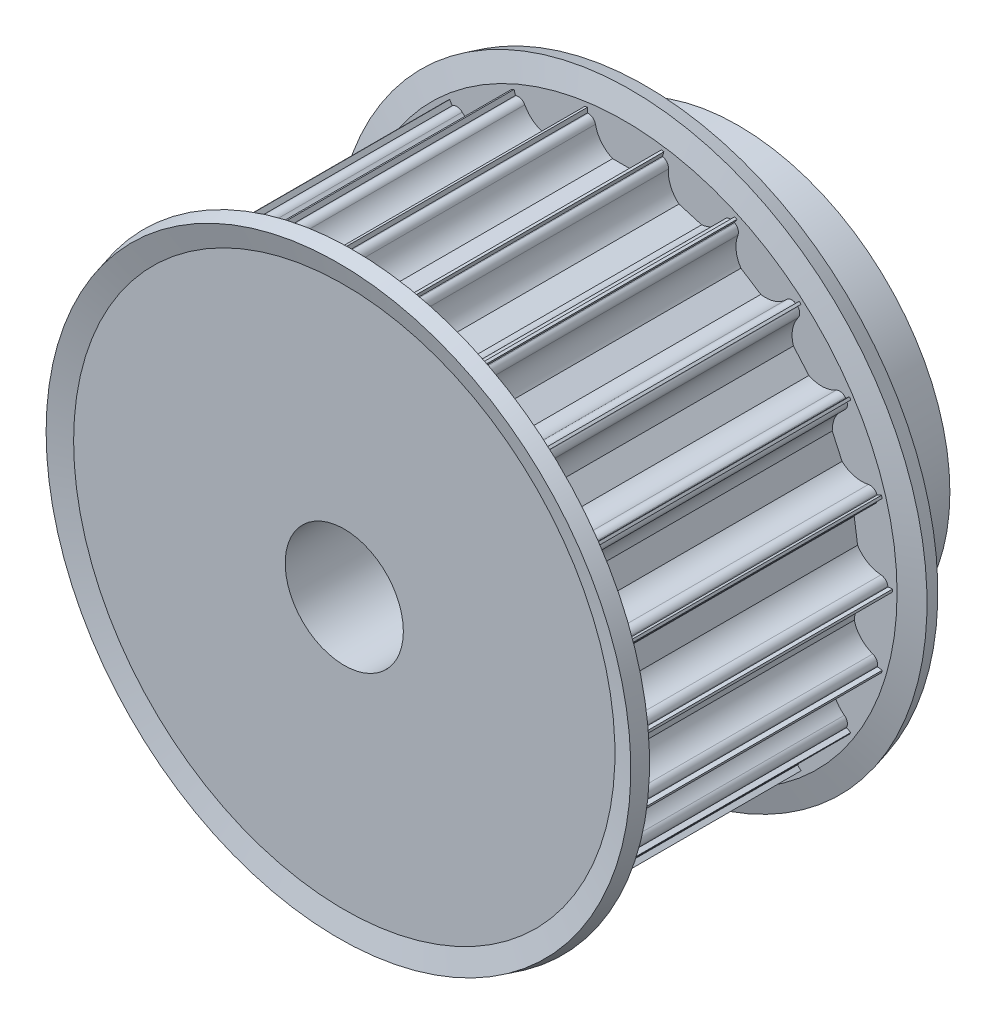
SolidWorks part; units mm, degrees
ref_plane "Front Plane" through (0, 0, 0) normal (0, 0, 1) x (1, 0, 0)
ref_plane "Top Plane" through (0, 0, 0) normal (0, 1, 0) x (1, 0, 0)
ref_plane "Right Plane" through (0, 0, 0) normal (1, 0, 0) x (0, 0, -1)
sketch "Sketch1" plane through (0, 0, 0) normal (1, 0, 0) x (0, 0, -1)
  line L0 (0, 0) -> (38.5259, 0) construction
  line L1 (0, 6) -> (40, 6)
  line L2 (40, 6) -> (40, 21.5)
  line L3 (40, 21.5) -> (30, 21.5)
  line L4 (30, 21.5) -> (30, 27.25)
  line L5 (30, 27.25) -> (0, 27.25)
  line L6 (0, 27.25) -> (0, 6)
  dimension "D1" = 27.25
  dimension "D2" = 6
  dimension "D3" = 30
  dimension "D4" = 10
  dimension "D5" = 15.5
revolve "Revolve1" add sketch "Sketch1" angle 360 about L0
sketch "Sketch2" plane through (0, 0, 0) normal (0, 0, 1) x (1, 0, 0)
  line L0 (-3.6742, 26.5) -> (-3.75, 26.5)
  line L1 (-3.75, 26.5) -> (-3.75, 28.5)
  line L2 (-3.75, 28.5) -> (3.75, 28.5)
  line L3 (3.75, 28.5) -> (3.75, 26.5)
  line L4 (3.6742, 26.5) -> (3.75, 26.5)
  line L5 (-1.199, 23.75) -> (1.199, 23.75)
  arc A0 (2.9394, 25.9) -> (1.199, 23.75) centre (0, 26.5) cw
  arc A1 (2.9394, 25.9) -> (3.6742, 26.5) centre (3.6742, 25.75) cw
  arc A2 (-2.9394, 25.9) -> (-3.6742, 26.5) centre (-3.6742, 25.75) ccw
  arc A3 (-1.199, 23.75) -> (-2.9394, 25.9) centre (0, 26.5) cw
  point P3 (0, 28.5)
  point P11 (3, 26.5)
  point P14 (-3, 26.5)
  dimension "D1" = 3
  dimension "D5" = 0.75
  dimension "D2" = 26.5
  dimension "D3" = 7.5
  dimension "D4" = 2
  dimension "D6" = 2.75
extrude "Cut-Extrude1" cut sketch "Sketch2" against normal up to next
pattern_circular "CirPattern1" count 22 over 360 about axis through (0, 0, 0) along (0, 0, 1) of "Cut-Extrude1"
sketch "Sketch3" plane through (0, 0, 0) normal (1, 0, 0) x (0, 0, -1)
  line L0 (15, 26.9539) -> (15, 7.4082) construction
  line L1 (30, 26.9539) -> (0, 26.9539) construction
  line L2 (30, 7.4082) -> (0, 7.4082) construction
  line L3 (30, 21.5) -> (30, 27.4856)
  line L4 (30, 20.628) -> (30, 23.3776) construction
  line L5 (30, -21.5) -> (30, 21.5) construction
  line L6 (30, 27.4856) -> (30.5902, 29.6881)
  line L7 (30.5902, 29.6881) -> (29.0902, 30.09)
  line L8 (29.0902, 30.09) -> (28.4471, 27.69)
  line L9 (28.4471, 27.69) -> (28.4471, 21.5)
  line L10 (28.4471, 21.5) -> (30, 21.5)
  line L11 (40, 21.5) -> (30, 21.5) construction
  line L12 (1.5529, 21.5) -> (0, 21.5)
  line L13 (1.5529, 27.69) -> (1.5529, 21.5)
  line L14 (0, 21.5) -> (0, 27.4856)
  line L15 (0, 27.4856) -> (-0.5902, 29.6881)
  line L16 (-0.5902, 29.6881) -> (0.9098, 30.09)
  line L17 (0.9098, 30.09) -> (1.5529, 27.69)
  line L18 (0, 0) -> (-11.2595, 0) construction
  dimension "D1" = 15
  dimension "D2" = 1.5
  dimension "D3" = 6.19
  dimension "D4" = 2.4
revolve "Revolve3" add sketch "Sketch3" angle 360 about L18
